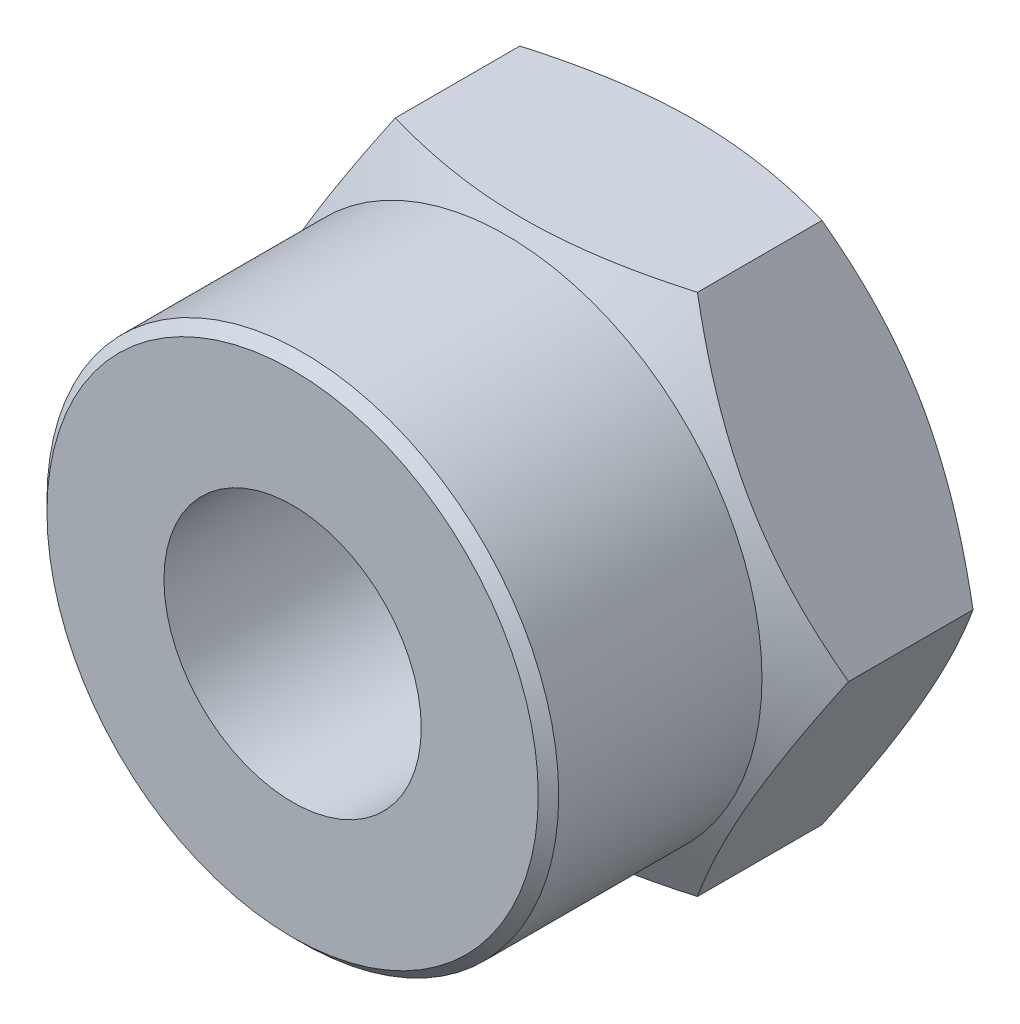
SolidWorks part; units mm, degrees
ref_plane "Front" through (0, 0, 0) normal (0, 0, 1) x (1, 0, 0)
ref_plane "Top" through (0, 0, 0) normal (0, 1, 0) x (1, 0, 0)
ref_plane "Right" through (0, 0, 0) normal (1, 0, 0) x (0, 0, -1)
sketch "Sketch1" plane through (0, 0, 0) normal (0, 0, 1) x (1, 0, 0)
  line L1 (2.8868, -5) -> (5.7735, 0)
  line L2 (5.7735, 0) -> (2.8868, 5)
  line L3 (2.8868, 5) -> (-2.8868, 5)
  line L4 (-2.8868, 5) -> (-5.7735, 0)
  line L5 (-5.7735, 0) -> (-2.8868, -5)
  line L6 (-2.8868, -5) -> (2.8868, -5)
  circle A0 centre (0, 0) radius 5 construction
  circle A1 centre (0, 0) radius 2.4585
  dimension "xd" = 4.917
  dimension "s" = 10
extrude "BaseNut" add sketch "Sketch1" against normal blind 3.92
cosmetic thread "ThreadCosmetic1" [suppressed] parameters "m"=4.9, "D2"=6
sketch "Sketch3" plane through (0, 0, 0) normal (0, 1, 0) x (1, 0, 0)
  line L0 (0, 16.3108) -> (0, -16.1137) construction
  line L2 (-2.0696, 1.96) -> (33.5085, 1.96) construction
  line L3 (4.44, 3.92) -> (5.7735, 3.92)
  line L5 (5.7735, 3.92) -> (5.7735, 3.1501)
  line L7 (5.7735, 3.1501) -> (4.44, 3.92)
  line L8 (5.7735, 0.7699) -> (4.44, 0)
  line L9 (5.7735, 0) -> (5.7735, 0.7699)
  line L10 (4.44, 0) -> (5.7735, 0)
  dimension "D1" = 30
  dimension "dw" = 8.88
revolve "Double-Chamfer" cut sketch "Sketch3" angle 360 about L0
sketch "Sketch2" plane through (20.0871, -4.2815, 0) normal (0, 0, 1) x (1, 0, 0)
  circle A1 centre (-20.0871, 4.2815) radius 2.4585 construction
  circle A2 centre (-20.0871, 4.2815) radius 4.89
  circle A3 centre (-20.0871, 4.2815) radius 2.4585
  dimension "s1" = 9.78
extrude "Extrude1" add sketch "Sketch2" along normal offset from surface (4.08 mm away) 8 up to face at (2.4585, 0, -3.92)
sketch "Sketch5" plane through (0, 0, 0) normal (0, 1, 0) x (1, 0, 0)
  line L0 (0, 16.8008) -> (0, -2.8116) construction
  line L2 (2.4585, 3.92) -> (3.375, 3.92)
  line L5 (3.375, 3.92) -> (2.4585, 3.0035)
  line L7 (2.4585, 3.0035) -> (2.4585, 3.92)
  dimension "D1" = 45
  dimension "da" = 6.75
revolve "EndChamfer" cut sketch "Sketch5" angle 360 about L0
chamfer "Chamfer1" distance 0.1956 angle 45 1 edges at (4.89, 0, 4.08)
sketch "Sketch6" plane through (0, 0, 0) normal (0, 1, 0) x (1, 0, 0)
  line L0 (0, 30.0005) -> (0, -32.7386) construction
  line L1 (1.917, 3.2743) -> (2.4585, 3.2743)
  line L2 (2.4585, 3.2743) -> (2.9275, 3.0035)
  line L3 (2.9275, 3.0035) -> (2.4585, 2.7328)
  line L4 (2.4585, 2.7328) -> (1.917, 2.7328)
  line L5 (1.917, 2.7328) -> (1.917, 3.2743)
  line L6 (-2.4585, 3.0035) -> (2.4585, 3.0035) construction
  dimension "D1" = 0.5415
  dimension "D2" = 4.917
revolve "Cut-Revolve10" [suppressed] cut sketch "Sketch6" angle 360 about L0
pattern_linear "LPattern10" [suppressed] count 6 spacing 0.6498 along (0, 0, 1)
equation "\"D1@Chamfer1\" = \"s1@Sketch2\" / 50"
equation "\"D2@Sketch6\" = \"xd@Sketch1\""
equation "\"D1@Sketch6\" = (  \"D2@ThreadCosmetic1\" - \"xd@Sketch1\" )  / 2"
equation "\"D3@LPattern10\" = \"D1@Sketch6\" * 1.2"
equation "\"D1@LPattern10\" = \"m1@BaseNut\" / \"D3@LPattern10\""
